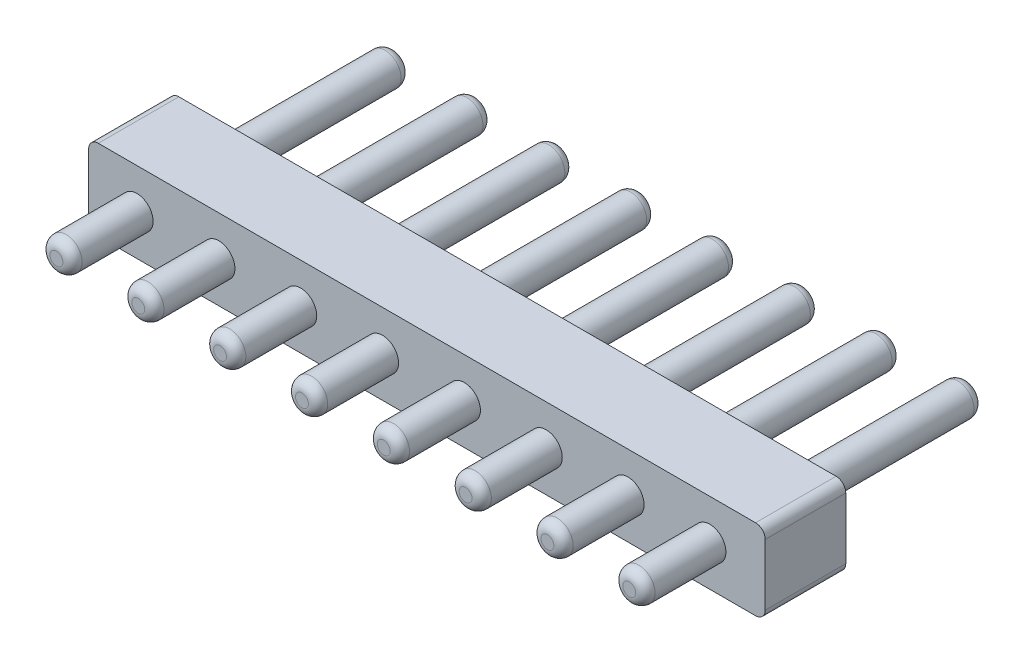
SolidWorks part; units mm, degrees
ref_plane "Front Plane" through (0, 0, 0) normal (0, 0, 1) x (1, 0, 0)
ref_plane "Top Plane" through (0, 0, 0) normal (0, 1, 0) x (1, 0, 0)
ref_plane "Right Plane" through (0, 0, 0) normal (1, 0, 0) x (0, 0, -1)
sketch "Sketch1" plane through (0, 0, 0) normal (0, 0, 1) x (1, 0, 0)
  line L1 (-10.5, 1.25) -> (10.5, 1.25)
  line L2 (-10.5, 1.25) -> (-10.5, -1.25)
  line L3 (-10.5, -1.25) -> (10.5, -1.25)
  line L4 (10.5, 1.25) -> (10.5, -1.25)
  line L5 (-10.5, 1.25) -> (10.5, -1.25) construction
  line L6 (-10.5, -1.25) -> (10.5, 1.25) construction
  point P0 (0, 0)
  dimension "D1" = 21
  dimension "D2" = 2.5
extrude "Boss-Extrude1" add sketch "Sketch1" along normal blind 2.5
sketch "Sketch2" plane through (0, 0, 2.5) normal (0, 0, 1) x (1, 0, 0)
  circle A0 centre (-9, 0) radius 0.5
  circle A1 centre (-6.46, 0) radius 0.5
  circle A2 centre (-3.92, 0) radius 0.5
  circle A3 centre (-1.38, 0) radius 0.5
  circle A4 centre (1.16, 0) radius 0.5
  circle A5 centre (3.7, 0) radius 0.5
  circle A6 centre (6.24, 0) radius 0.5
  circle A7 centre (8.78, 0) radius 0.5
  dimension "D1" = 1
  dimension "D2" = 9
  dimension "D3" = 8
extrude "Boss-Extrude2" add sketch "Sketch2" along normal blind 2.5 and the other way blind 8
fillet "Fillet1" radius 0.3 16 edges at (9.28, 0, -5.5) (6.74, 0, -5.5) (4.2, 0, -5.5) (1.66, 0, -5.5) (-0.88, 0, -5.5) (-3.42, 0, -5.5) (-5.96, 0, -5.5) (-8.5, 0, -5.5) (9.28, 0, 5) (6.74, 0, 5) (4.2, 0, 5) (1.66, 0, 5) (-0.88, 0, 5) (-3.42, 0, 5) (-5.96, 0, 5) (-8.5, 0, 5)
fillet "Fillet2" radius 0.3 4 edges at (10.5, 1.25, 1.25) (10.5, -1.25, 1.25) (-10.5, 1.25, 1.25) (-10.5, -1.25, 1.25)
